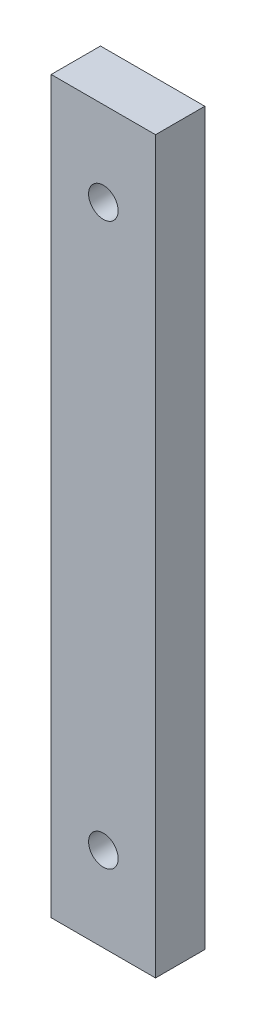
SolidWorks part; units mm, degrees
ref_plane "Front Plane" through (0, 0, 0) normal (0, 0, 1) x (1, 0, 0)
ref_plane "Top Plane" through (0, 0, 0) normal (0, 1, 0) x (1, 0, 0)
ref_plane "Right Plane" through (0, 0, 0) normal (1, 0, 0) x (0, 0, -1)
sketch "Sketch1" plane through (0, 0, 0) normal (0, 0, 1) x (1, 0, 0)
  line L0 (-6.35, -44.45) -> (6.35, -44.45)
  line L1 (6.35, -44.45) -> (6.35, 44.45)
  line L2 (6.35, 44.45) -> (-6.35, 44.45)
  line L3 (-6.35, 44.45) -> (-6.35, -44.45)
  circle A0 centre (0, 34.15) radius 1.8
  circle A1 centre (0, -34.15) radius 1.8
extrude "Boss-Extrude1" add sketch "Sketch1" along normal blind 6
